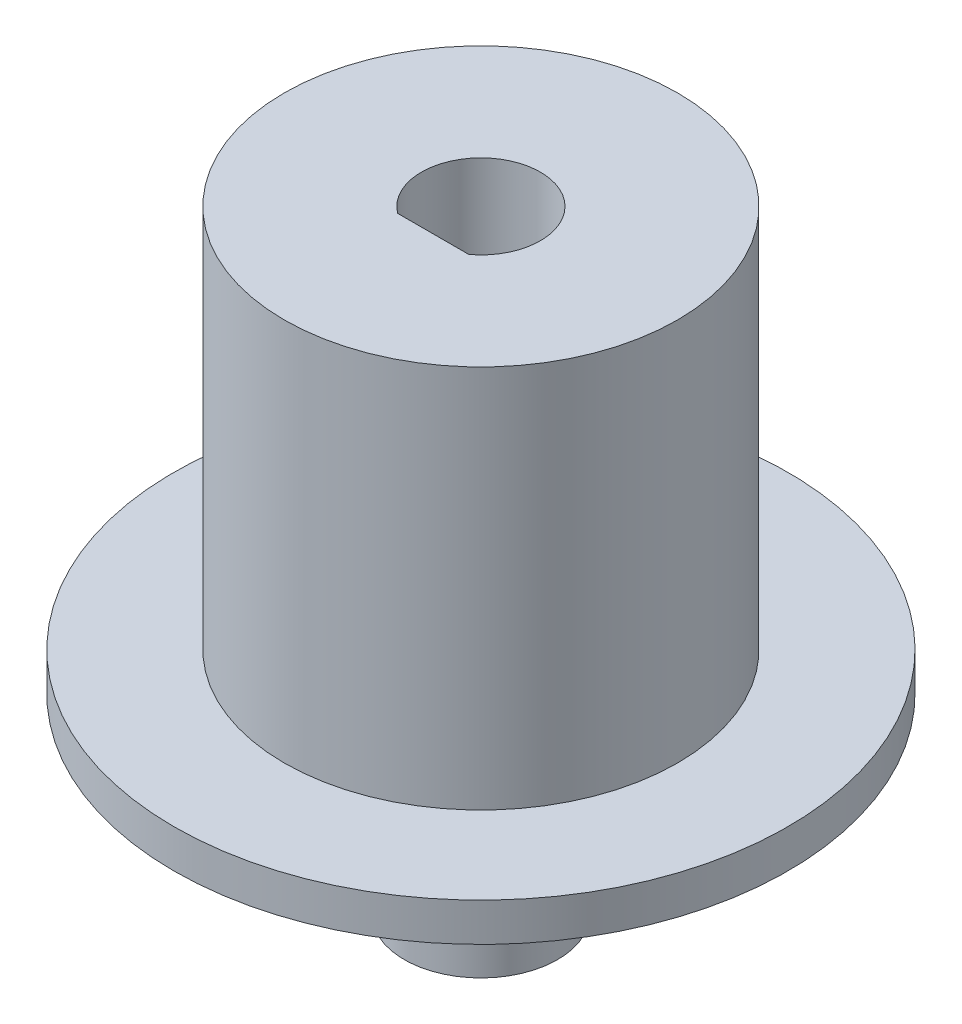
SolidWorks part; units mm, degrees
ref_plane "Front Plane" through (0, 0, 0) normal (0, 0, 1) x (1, 0, 0)
ref_plane "Top Plane" through (0, 0, 0) normal (0, 1, 0) x (1, 0, 0)
ref_plane "Right Plane" through (0, 0, 0) normal (1, 0, 0) x (0, 0, -1)
sketch "Sketch1" plane through (0, 0, 0) normal (0, 1, 0) x (1, 0, 0)
  circle A0 centre (0, 0) radius 16
  dimension "D1" = 32
extrude "Boss-Extrude1" add sketch "Sketch1" along normal blind 2
sketch "Sketch2" plane through (0, 2, 0) normal (0, 1, 0) x (1, 0, 0)
  circle A0 centre (0, 0) radius 10.25
  dimension "D1" = 20.5
extrude "Boss-Extrude2" add sketch "Sketch2" along normal blind 20
sketch "Sketch4" plane through (0, 0, 0) normal (0, -1, 0) x (1, 0, 0)
  circle A0 centre (0, 0) radius 4
extrude "Boss-Extrude3" add sketch "Sketch4" along normal blind 10
sketch "Sketch3" plane through (0, 0, 0) normal (0, -1, 0) x (1, 0, 0)
  line L0 (0, -3.1) -> (0, 2.4847)
  line L1 (0, 2.4847) -> (-1.8538, 2.4847)
  line L2 (0, 2.4847) -> (1.8538, 2.4847)
  circle A0 centre (0, 0) radius 3.1
extrude "Cut-Extrude1" cut sketch "Sketch3" against normal through all both and the other way through all contours L0 A0 L2 | L1 A0 L0
